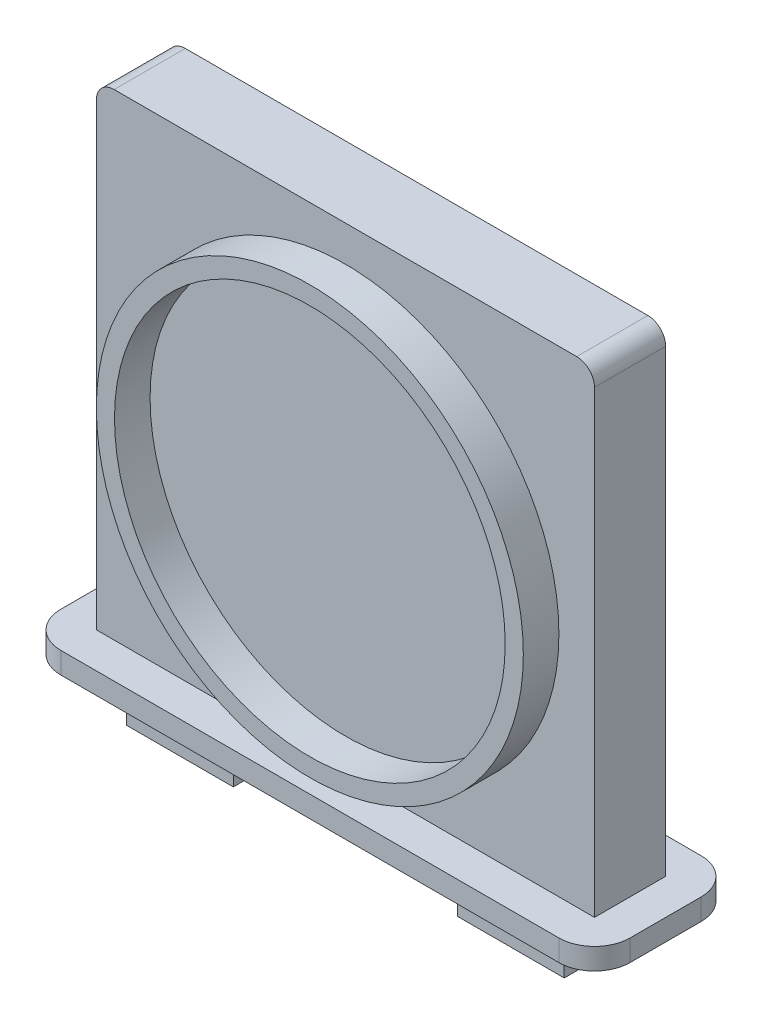
SolidWorks part; units mm, degrees
ref_plane "Front Plane" through (0, 0, 0) normal (0, 0, 1) x (1, 0, 0)
ref_plane "Top Plane" through (0, 0, 0) normal (0, 1, 0) x (1, 0, 0)
ref_plane "Right Plane" through (0, 0, 0) normal (1, 0, 0) x (0, 0, -1)
sketch "Sketch1" plane through (0, 0, 0) normal (0, 0, 1) x (1, 0, 0)
  line L1 (-35, 35) -> (35, 35)
  line L2 (-35, 35) -> (-35, -35)
  line L3 (-35, -35) -> (35, -35)
  line L4 (35, 35) -> (35, -35)
  line L5 (-35, 35) -> (35, -35) construction
  line L6 (-35, -35) -> (35, 35) construction
  point P0 (0, 0)
  dimension "D1" = 70
  dimension "D2" = 70
extrude "Boss-Extrude1" add sketch "Sketch1" along normal blind 10
sketch "Sketch2" plane through (0, 0, 10) normal (0, 0, 1) x (1, 0, 0)
  circle A4 centre (0, 0) radius 27.45
  circle A5 centre (0, 0) radius 30
  dimension "D1" = 54.9
  dimension "D2" = 60
extrude "Boss-Extrude2" add sketch "Sketch2" along normal blind 5
fillet "Fillet1" radius 2.5 2 edges at (35, 35, 5) (-35, 35, 5)
sketch "Sketch3" plane through (0, 0, 0) normal (0, 0, -1) x (-1, 0, 0)
  line L0 (0, -35) -> (0, -45) construction
  line L1 (35, -35) -> (-35, -35) construction
  line L9 (-20.75, -38.5) -> (-15.75, -38.5)
  line L10 (-30.75, -38.5) -> (-25.75, -38.5)
  line L11 (-30.75, -38.5) -> (-30.75, -41.5)
  line L12 (-30.75, -41.5) -> (-15.75, -41.5)
  line L13 (-15.75, -38.5) -> (-15.75, -41.5)
  line L14 (-30.75, -38.5) -> (-15.75, -41.5) construction
  line L15 (-30.75, -41.5) -> (-15.75, -38.5) construction
  line L16 (-25.75, -35) -> (-20.75, -35)
  line L17 (-25.75, -35) -> (-25.75, -38.5)
  line L19 (-20.75, -35) -> (-20.75, -38.5)
  line L20 (-25.75, -35) -> (-20.75, -38.5) construction
  line L21 (-25.75, -38.5) -> (-20.75, -35) construction
  line L22 (30.75, -38.5) -> (30.75, -41.5)
  line L23 (30.75, -41.5) -> (15.75, -41.5)
  line L24 (15.75, -38.5) -> (15.75, -41.5)
  line L25 (20.75, -38.5) -> (15.75, -38.5)
  line L26 (20.75, -35) -> (20.75, -38.5)
  line L27 (25.75, -35) -> (20.75, -35)
  line L28 (25.75, -35) -> (25.75, -38.5)
  line L29 (30.75, -38.5) -> (25.75, -38.5)
  point P5 (0, -40)
  point P12 (-23.25, -40)
  point P17 (-23.25, -36.75)
  dimension "D3" = 3
  dimension "D4" = 15
  dimension "D5" = 5
  dimension "D6" = 3.5
extrude "Boss-Extrude3" add sketch "Sketch3" against normal blind 10
sketch "Sketch5" plane through (0, -35, 0) normal (0, -1, 0) x (1, 0, 0)
  line L0 (0, 10) -> (0, 0) construction
  line L1 (-20.75, 10) -> (20.75, 10) construction
  line L2 (5, -5) -> (35, -5)
  line L3 (-35, 10) -> (35, 10)
  line L4 (-35, 10) -> (-35, 0)
  line L5 (-35, 0) -> (35, 0)
  line L6 (35, 10) -> (35, 0)
  line L7 (-35, 10) -> (35, 0) construction
  line L8 (-35, 0) -> (35, 10) construction
  line L9 (-35, 15) -> (35, 15)
  line L10 (-40, 10) -> (-40, 0)
  line L11 (-35, -5) -> (-5, -5)
  line L12 (40, 10) -> (40, 0)
  line L13 (-40, 15) -> (40, -5) construction
  line L14 (-40, -5) -> (40, 15) construction
  line L16 (-5, -5) -> (-5, -5.5)
  line L17 (-4.5, -6) -> (4.5, -6)
  line L18 (5, -5) -> (5, -5.5)
  line L19 (0, 0) -> (0, -6) construction
  arc A0 (35, 15) -> (40, 10) centre (35, 10) cw
  arc A1 (35, -5) -> (40, 0) centre (35, 0) ccw
  arc A2 (-40, 0) -> (-35, -5) centre (-35, 0) ccw
  arc A3 (-35, 15) -> (-40, 10) centre (-35, 10) ccw
  circle A4 centre (0, -3) radius 1.5
  arc A5 (-5, -5.5) -> (-4.5, -6) centre (-4.5, -5.5) ccw
  arc A6 (4.5, -6) -> (5, -5.5) centre (4.5, -5.5) ccw
  point P5 (0, 5)
  point P11 (0, 5)
  point P37 (-5, -6)
  dimension "D3" = 5
  dimension "D6" = 3
  dimension "D7" = 0.5
  dimension "D1" = 20
  dimension "D2" = 80
  dimension "D4" = 1
  dimension "D5" = 10
extrude "Boss-Extrude5" add sketch "Sketch5" against normal blind 3
